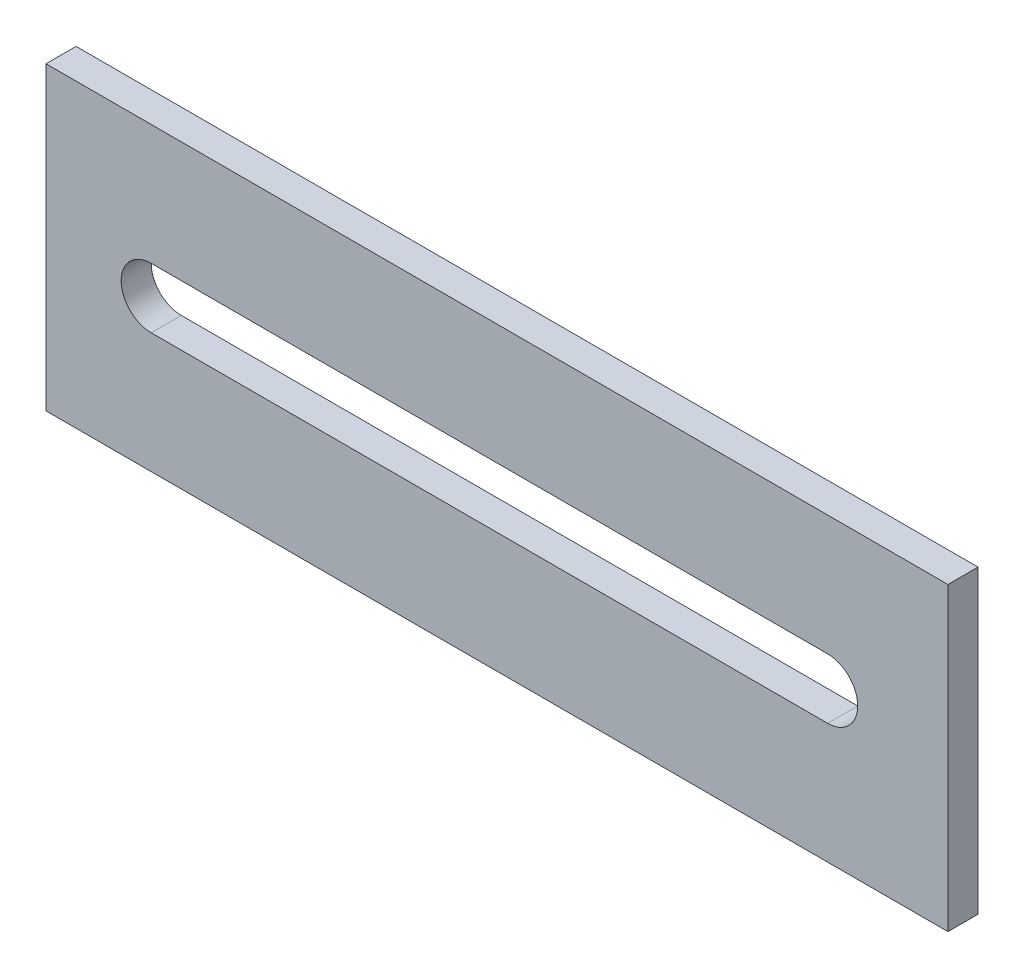
SolidWorks part; units mm, degrees
ref_plane "Front Plane" through (0, 0, 0) normal (0, 0, 1) x (1, 0, 0)
ref_plane "Top Plane" through (0, 0, 0) normal (0, 1, 0) x (1, 0, 0)
ref_plane "Right Plane" through (0, 0, 0) normal (1, 0, 0) x (0, 0, -1)
sketch "Sketch1" plane through (0, 0, 0) normal (0, 0, 1) x (1, 0, 0)
  line L1 (-30, 10) -> (30, 10)
  line L2 (-30, 10) -> (-30, -10)
  line L3 (-30, -10) -> (30, -10)
  line L4 (30, 10) -> (30, -10)
  line L5 (-30, 10) -> (30, -10) construction
  line L6 (-30, -10) -> (30, 10) construction
  point P0 (0, 0)
  dimension "D1" = 60
  dimension "D2" = 20
extrude "Boss-Extrude1" add sketch "Sketch1" along normal blind 2
sketch "Sketch2" plane through (0, 0, 2) normal (0, 0, 1) x (1, 0, 0)
  line L0 (-23, 0) -> (22, 0) construction
  line L1 (-23, 2) -> (22, 2)
  line L2 (-23, -2) -> (22, -2)
  line L3 (-30, 10) -> (-30, -10) construction
  arc A0 (-23, 2) -> (-23, -2) centre (-23, 0) ccw
  arc A1 (22, -2) -> (22, 2) centre (22, 0) ccw
  point P3 (-0.5, 0)
  dimension "D1" = 2
  dimension "D2" = 45
  dimension "D3" = 7
extrude "Cut-Extrude1" cut sketch "Sketch2" against normal blind 2
